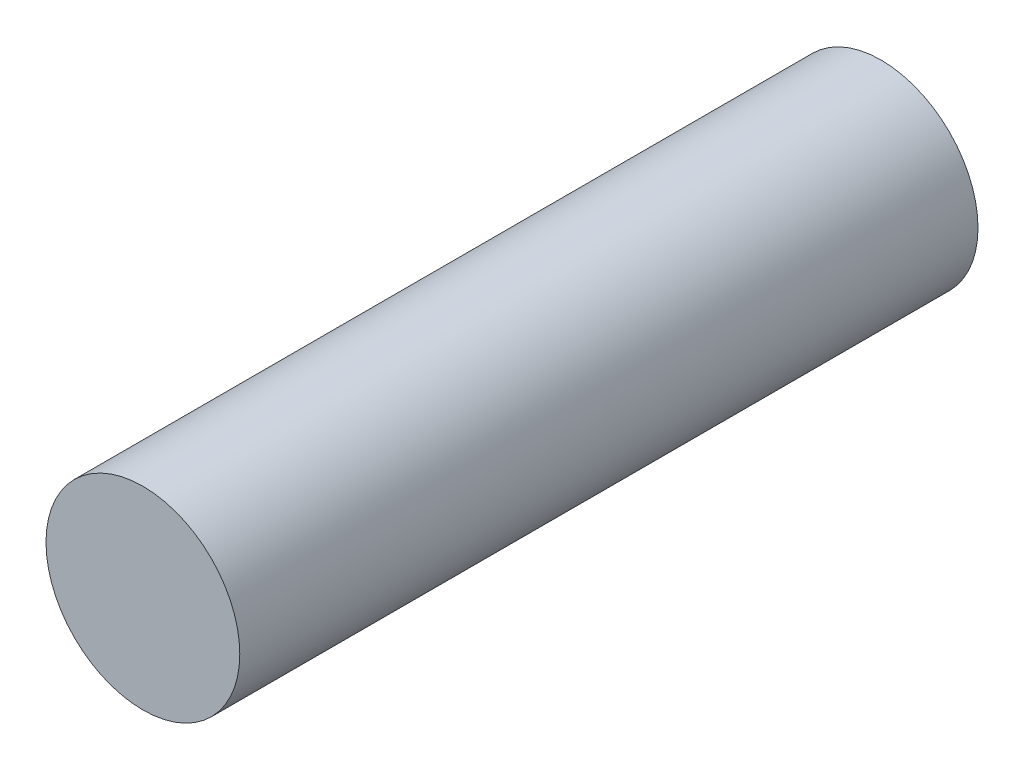
SolidWorks part; units mm, degrees
ref_plane "Front Plane" through (0, 0, 0) normal (0, 0, 1) x (1, 0, 0)
ref_plane "Top Plane" through (0, 0, 0) normal (0, 1, 0) x (1, 0, 0)
ref_plane "Right Plane" through (0, 0, 0) normal (1, 0, 0) x (0, 0, -1)
sketch "Sketch1" plane through (0, 0, 0) normal (0, 0, 1) x (1, 0, 0)
  circle A0 centre (0, 0) radius 5.25
  dimension "D1" = 10.5
extrude "Boss-Extrude1" add sketch "Sketch1" along normal blind 40
